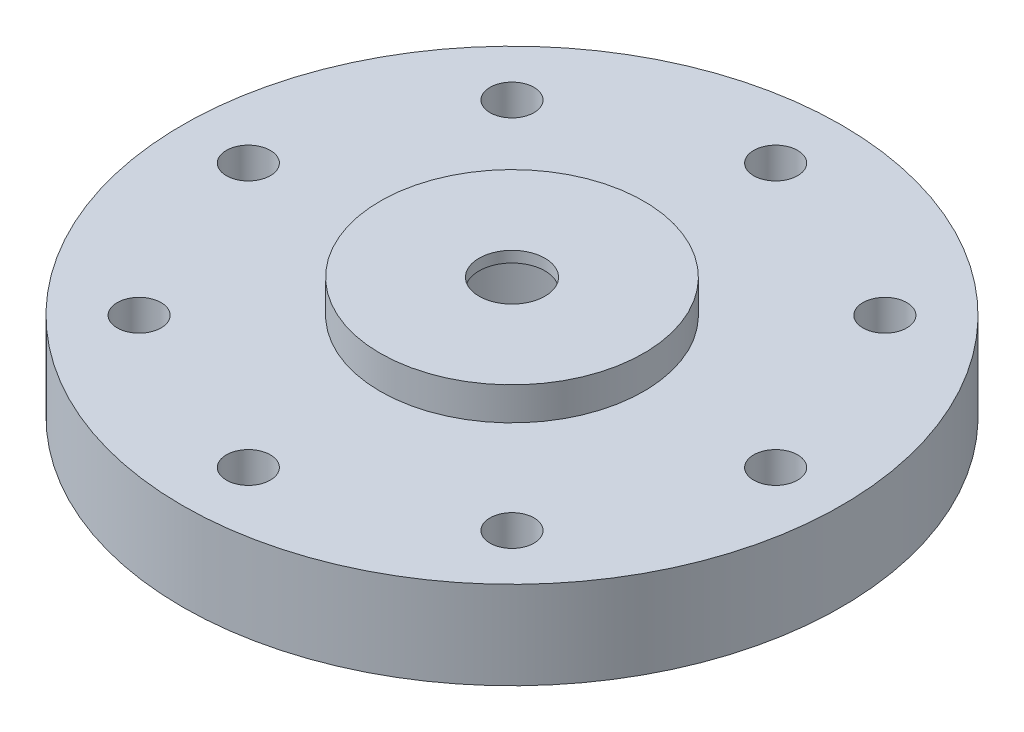
SolidWorks part; units mm, degrees
material "1060 合金"
ref_plane "前视基准面" through (0, 0, 0) normal (0, 0, 1) x (1, 0, 0)
ref_plane "上视基准面" through (0, 0, 0) normal (0, 1, 0) x (1, 0, 0)
ref_plane "右视基准面" through (0, 0, 0) normal (1, 0, 0) x (0, 0, -1)
other "Configuration Table"
sketch "草图1" plane through (0, 0, 0) normal (0, 1, 0) x (1, 0, 0)
  line L0 (0, 0) -> (26.6948, 0) construction
  line L1 (0, 0) -> (0, 19.2144) construction
  line L2 (0, 0) -> (17.676, 17.676) construction
  circle A0 centre (0, 0) radius 15
  circle A1 centre (0, 12) radius 1
  circle A2 centre (8.4853, 8.4853) radius 1
  circle A3 centre (8.4853, -8.4853) radius 1
  circle A4 centre (0, -12) radius 1
  circle A5 centre (-8.4853, -8.4853) radius 1
  circle A6 centre (-8.4853, 8.4853) radius 1
  circle A7 centre (-12, 0) radius 1
  circle A8 centre (12, 0) radius 1
  circle A9 centre (0, 0) radius 1.5
  dimension "D1" = 30
  dimension "D3" = 2
  dimension "D4" = 2
  dimension "D5" = 24
  dimension "D6" = 24
  dimension "D7" = 3
  dimension "D2" = 45
extrude "凸台-拉伸1" add sketch "草图1" along normal blind 4
sketch "草图2" plane through (0, 4, 0) normal (0, 1, 0) x (1, 0, 0)
  circle A0 centre (0, 0) radius 6
  circle A1 centre (0, 0) radius 1.5
  dimension "D1" = 12
  dimension "D2" = 3
extrude "凸台-拉伸2" add sketch "草图2" along normal blind 1.5
sketch "草图3" plane through (0, 0, 0) normal (0, -1, 0) x (1, 0, 0)
  circle A0 centre (0, 0) radius 4.5
  dimension "D1" = 9
extrude "切除-拉伸1" cut sketch "草图3" against normal blind 5
